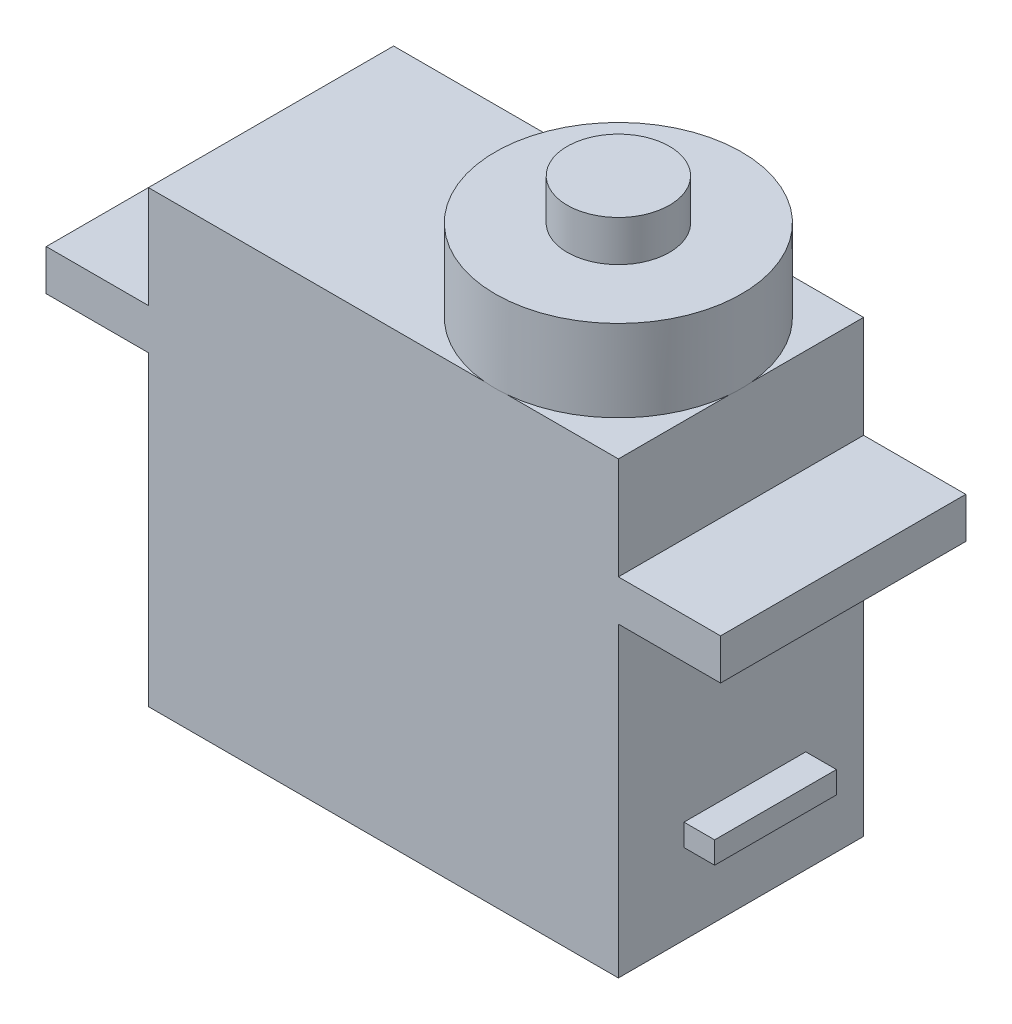
SolidWorks part; units mm, degrees
material "尼龙 101"
ref_plane "前视基准面" through (0, 0, 0) normal (0, 0, 1) x (1, 0, 0)
ref_plane "上视基准面" through (0, 0, 0) normal (0, 1, 0) x (1, 0, 0)
ref_plane "右视基准面" through (0, 0, 0) normal (1, 0, 0) x (0, 0, -1)
sketch "草图1" plane through (0, 0, 0) normal (0, 1, 0) x (1, 0, 0)
  line L1 (0, 0) -> (23, 0)
  line L2 (0, 0) -> (0, 12)
  line L3 (0, 12) -> (23, 12)
  line L4 (23, 0) -> (23, 12)
extrude "凸台-拉伸1" add sketch "草图1" along normal blind 22
sketch "草图2" plane through (23, 0, 0) normal (1, 0, 0) x (0, 0, -1)
  line L0 (-3.026, 15) -> (15.1552, 15) construction
  line L1 (0, 0) -> (12, 0) construction
  line L2 (-10.7071, 17) -> (18.432, 17) construction
  line L3 (0, 22) -> (0, 0) construction
  line L4 (0, 17) -> (12, 17)
  line L5 (0, 17) -> (0, 15)
  line L6 (0, 15) -> (12, 15)
  line L7 (12, 17) -> (12, 15)
  line L8 (12, 22) -> (12, 0) construction
  dimension "D1" = 15
  dimension "D2" = 2
extrude "凸台-拉伸2" add sketch "草图2" along normal blind 5
sketch "草图3" plane through (23, 0, 0) normal (1, 0, 0) x (0, 0, -1)
  line L0 (-3.3959, 4) -> (14.9555, 4) construction
  line L1 (15.807, 5) -> (-3.3959, 5) construction
  line L2 (3.2106, 5.2597) -> (3.2106, 2.2941) construction
  line L3 (9.1711, 5.5533) -> (9.1711, 2.2941) construction
  line L4 (0, 0) -> (12, 0) construction
  line L6 (3.2106, 5) -> (9.1711, 5)
  line L7 (3.2106, 5) -> (3.2106, 3.9237)
  line L8 (3.2106, 3.9237) -> (9.1711, 3.9237)
  line L9 (9.1711, 5) -> (9.1711, 3.9237)
  dimension "D1" = 4
  dimension "D2" = 5
extrude "凸台-拉伸3" add sketch "草图3" along normal blind 1.5
sketch "草图4" plane through (0, 0, 0) normal (-1, 0, 0) x (0, 0, 1)
  line L0 (-15.9538, 15) -> (3.6308, 15) construction
  line L1 (2.75, 17) -> (-14.6912, 17) construction
  line L2 (-12, 0) -> (0, 0) construction
  line L3 (0, 22) -> (0, 0) construction
  line L4 (-12, 17) -> (0, 17)
  line L5 (-12, 17) -> (-12, 15)
  line L6 (-12, 15) -> (0, 15)
  line L7 (0, 17) -> (0, 15)
  dimension "D1" = 15
  dimension "D2" = 2
extrude "凸台-拉伸4" add sketch "草图4" along normal blind 5
sketch "草图5" plane through (0, 22, 0) normal (0, 1, 0) x (1, 0, 0)
  line L0 (0, 0) -> (23, 0) construction
  line L1 (23, 12) -> (11, 12) construction
  line L2 (23, 12) -> (23, 0) construction
  line L3 (23, 0) -> (11, 0) construction
  line L4 (11, 12) -> (11, 0) construction
  line L5 (11, 12) -> (23, 0) construction
  line L6 (23, 12) -> (11, 0) construction
  circle A0 centre (17, 6) radius 6.025
extrude "凸台-拉伸5" add sketch "草图5" along normal blind 4
sketch "草图6" plane through (0, 26, 0) normal (0, 1, 0) x (1, 0, 0)
  circle A0 centre (17, 6) radius 2.5
  point P0 (17, 6)
extrude "凸台-拉伸6" add sketch "草图6" along normal blind 2
